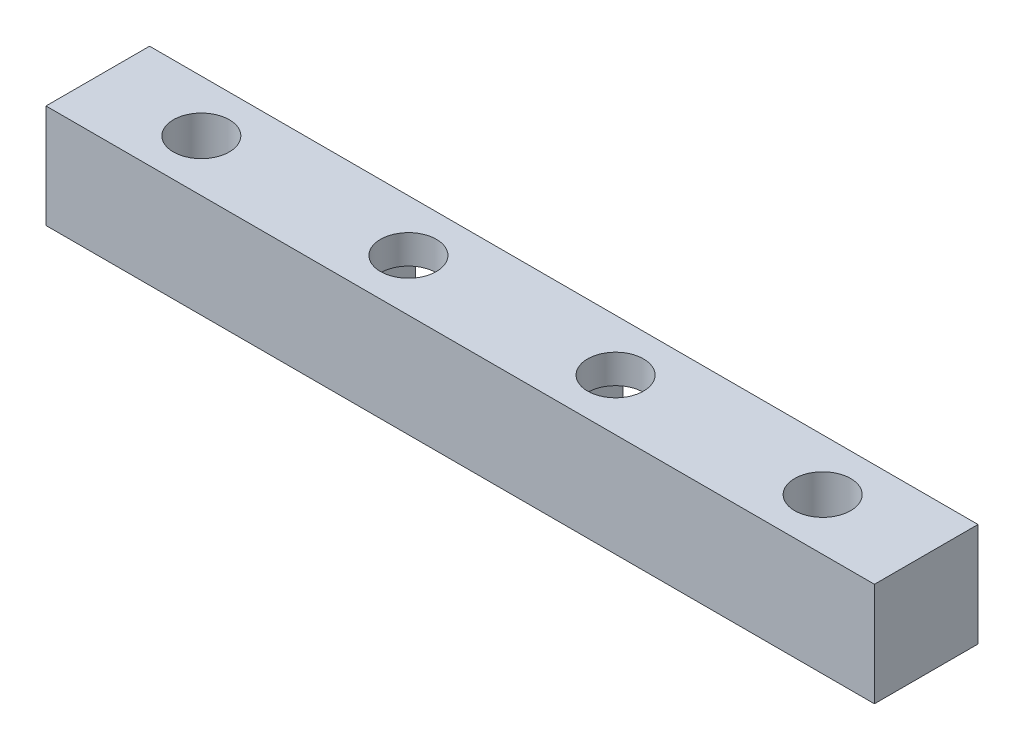
SolidWorks part; units mm, degrees
ref_plane "Front Plane" through (0, 0, 0) normal (0, 0, 1) x (1, 0, 0)
ref_plane "Top Plane" through (0, 0, 0) normal (0, 1, 0) x (1, 0, 0)
ref_plane "Right Plane" through (0, 0, 0) normal (1, 0, 0) x (0, 0, -1)
sketch "Sketch1" plane through (0, 0, 0) normal (0, 1, 0) x (1, 0, 0)
  line L1 (-50.8, 12.7) -> (50.8, 12.7)
  line L2 (-50.8, 12.7) -> (-50.8, 0)
  line L3 (-50.8, 0) -> (50.8, 0)
  line L4 (50.8, 12.7) -> (50.8, 0)
  point P4 (0, 0)
  dimension "D1" = 101.6
  dimension "D2" = 12.7
extrude "Boss-Extrude1" add sketch "Sketch1" along normal blind 12.7
sketch "Sketch2" plane through (0, 12.7, 0) normal (0, 1, 0) x (1, 0, 0)
  line L0 (-50.8, 6.35) -> (50.8, 6.35) construction
  line L1 (-50.8, 12.7) -> (-50.8, 0) construction
  line L2 (50.8, 0) -> (50.8, 12.7) construction
  circle A0 centre (-38.1, 6.35) radius 3.429
  circle A1 centre (38.1, 6.35) radius 3.429
  circle A2 centre (-12.7, 6.35) radius 3.429
  circle A3 centre (12.7, 6.35) radius 3.429
  dimension "D1" = 6.858
  dimension "D4" = 25.4
  dimension "D5" = 25.4
  dimension "D2" = 12.7
  dimension "D3" = 25.4
extrude "Cut-Extrude1" cut sketch "Sketch2" against normal through all
ref_plane "Plane1" through (0, 6.35, 0) normal (0, 1, 0) x (1, 0, 0)
sketch "Sketch3" plane through (0, 6.35, 0) normal (0, 1, 0) x (1, 0, 0)
  line L0 (-18.161, 3.1971) -> (-18.161, 19.3961)
  line L1 (-12.7, 0.0442) -> (-7.239, 3.1971)
  line L2 (-7.239, 3.1971) -> (-7.239, 9.5029)
  line L3 (-7.239, 9.5029) -> (-12.7, 12.6558) construction
  line L4 (-12.7, 12.6558) -> (-18.161, 9.5029) construction
  line L5 (-18.161, 9.5029) -> (-18.161, 3.1971) construction
  line L6 (-18.161, 3.1971) -> (-12.7, 0.0442)
  line L7 (-18.161, 19.3961) -> (-7.239, 19.3961)
  line L8 (-7.239, 19.3961) -> (-7.239, 9.5029)
  line L9 (7.239, 19.3961) -> (18.161, 19.3961)
  line L10 (18.161, 19.3961) -> (18.161, 9.5029)
  line L11 (18.161, 3.1971) -> (18.161, 9.5029)
  line L12 (12.7, 0.0442) -> (18.161, 3.1971)
  line L13 (7.239, 3.1971) -> (12.7, 0.0442)
  line L14 (7.239, 3.1971) -> (7.239, 19.3961)
  circle A0 centre (-12.7, 6.35) radius 5.461 construction
  circle A1 centre (-12.7, 6.35) radius 3.429 construction
  point P14 (-12.7, 0)
  dimension "D1" = 10.922
  dimension "D2" = 2
extrude "Cut-Extrude2" cut sketch "Sketch3" against normal mid plane 5.588
